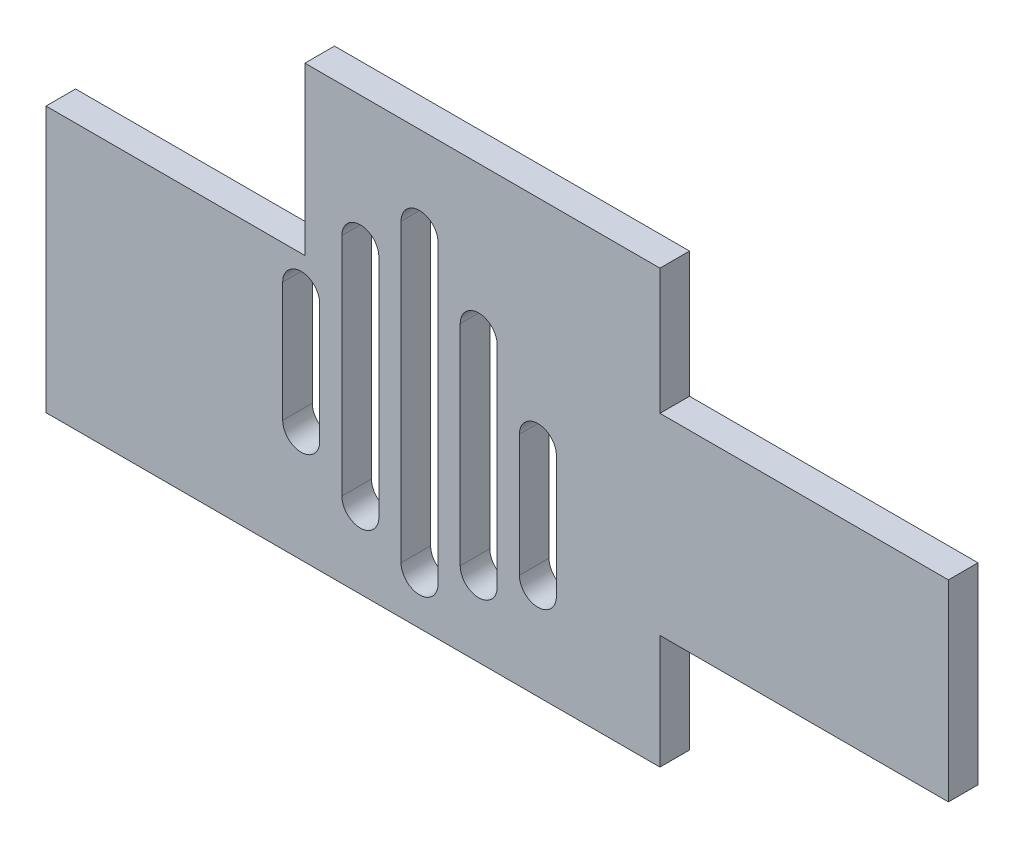
SolidWorks part; units mm, degrees
ref_plane "Front Plane" through (0, 0, 0) normal (0, 0, 1) x (1, 0, 0)
ref_plane "Top Plane" through (0, 0, 0) normal (0, 1, 0) x (1, 0, 0)
ref_plane "Right Plane" through (0, 0, 0) normal (1, 0, 0) x (0, 0, -1)
sketch "Sketch1" plane through (0, 0, 0) normal (0, 0, 1) x (1, 0, 0)
  line L0 (-4.1373, 38.9941) -> (-4.1373, -1.0059)
  line L6 (30.8627, 33.9941) -> (69.8627, 33.9941)
  line L9 (0.8627, 38.9941) -> (0.8627, -1.0059)
  line L12 (-12.1373, 33.3124) -> (-12.1373, 2.8098)
  line L15 (-7.1373, 33.3124) -> (-7.1373, 2.8098)
  line L18 (-15.1373, 23.8613) -> (-15.1373, 7.6834)
  line L21 (30.8627, 7.9941) -> (69.8627, 7.9941)
  line L62 (-17.1373, 50.9941) -> (-17.1373, 28.4723)
  line L63 (-17.1373, 28.4723) -> (-52.1373, 28.4723)
  line L65 (-52.1373, 28.4723) -> (-52.1373, -7.4309)
  line L66 (30.8627, 50.9941) -> (30.8627, 33.9941)
  line L68 (69.8627, 33.9941) -> (69.8627, 7.9941)
  line L70 (30.8627, 7.9941) -> (30.8627, -7.4309)
  line L71 (30.8627, 50.9941) -> (-17.1373, 50.9941)
  line L72 (30.8627, -7.4309) -> (-52.1373, -7.4309)
  line L75 (-20.1373, 23.8613) -> (-20.1373, 7.6834)
  line L77 (3.8627, 30.9941) -> (3.8627, 2.6474)
  line L79 (8.8627, 30.9941) -> (8.8627, 2.6474)
  line L80 (11.8627, 22.0483) -> (11.8627, 5.5385)
  line L81 (16.8627, 22.0483) -> (16.8627, 5.5385)
  circle A13 centre (-1.6373, 38.9941) radius 2.5 construction
  circle A14 centre (-1.6373, -1.0059) radius 2.5 construction
  arc A15 (-4.1373, 38.9941) -> (0.8627, 38.9941) centre (-1.6373, 38.9941) cw
  arc A16 (0.8627, -1.0059) -> (-4.1373, -1.0059) centre (-1.6373, -1.0059) cw
  circle A17 centre (6.3627, 30.9941) radius 2.5 construction
  circle A18 centre (6.3627, 2.6474) radius 2.5 construction
  circle A19 centre (-9.6373, 33.3124) radius 2.5 construction
  circle A20 centre (-9.6373, 2.8098) radius 2.5 construction
  circle A21 centre (-17.6373, 23.8613) radius 2.5 construction
  circle A22 centre (-17.6373, 7.6834) radius 2.5 construction
  circle A23 centre (14.3627, 22.0483) radius 2.5 construction
  circle A24 centre (14.3627, 5.5385) radius 2.5 construction
  arc A27 (-12.1373, 33.3124) -> (-7.1373, 33.3124) centre (-9.6373, 33.3124) cw
  arc A28 (-15.1373, 23.8613) -> (-20.1373, 23.8613) centre (-17.6373, 23.8613) ccw
  arc A29 (-20.1373, 7.6834) -> (-15.1373, 7.6834) centre (-17.6373, 7.6834) ccw
  arc A30 (-12.1373, 2.8098) -> (-7.1373, 2.8098) centre (-9.6373, 2.8098) ccw
  arc A31 (3.8627, 2.6474) -> (8.8627, 2.6474) centre (6.3627, 2.6474) ccw
  arc A32 (11.8627, 5.5385) -> (16.8627, 5.5385) centre (14.3627, 5.5385) ccw
  arc A33 (16.8627, 22.0483) -> (11.8627, 22.0483) centre (14.3627, 22.0483) ccw
  arc A34 (8.8627, 30.9941) -> (3.8627, 30.9941) centre (6.3627, 30.9941) ccw
  point P0 (0, 0)
  dimension "D3" = 5
  dimension "D4" = 3
  dimension "D5" = 3
  dimension "D6" = 3
  dimension "D7" = 3
  dimension "D9" = 12
  dimension "D8" = 26
  dimension "D10" = 13
  dimension "D11" = 58.4249
  dimension "D12" = 8
  dimension "D13" = 17
  dimension "D14" = 35
  dimension "D15" = 39
  dimension "D16" = 48
  dimension "D23" = 40
extrude "Boss-Extrude1" add sketch "Sketch1" along normal blind 4
equation "\"m\"= 3mm"
